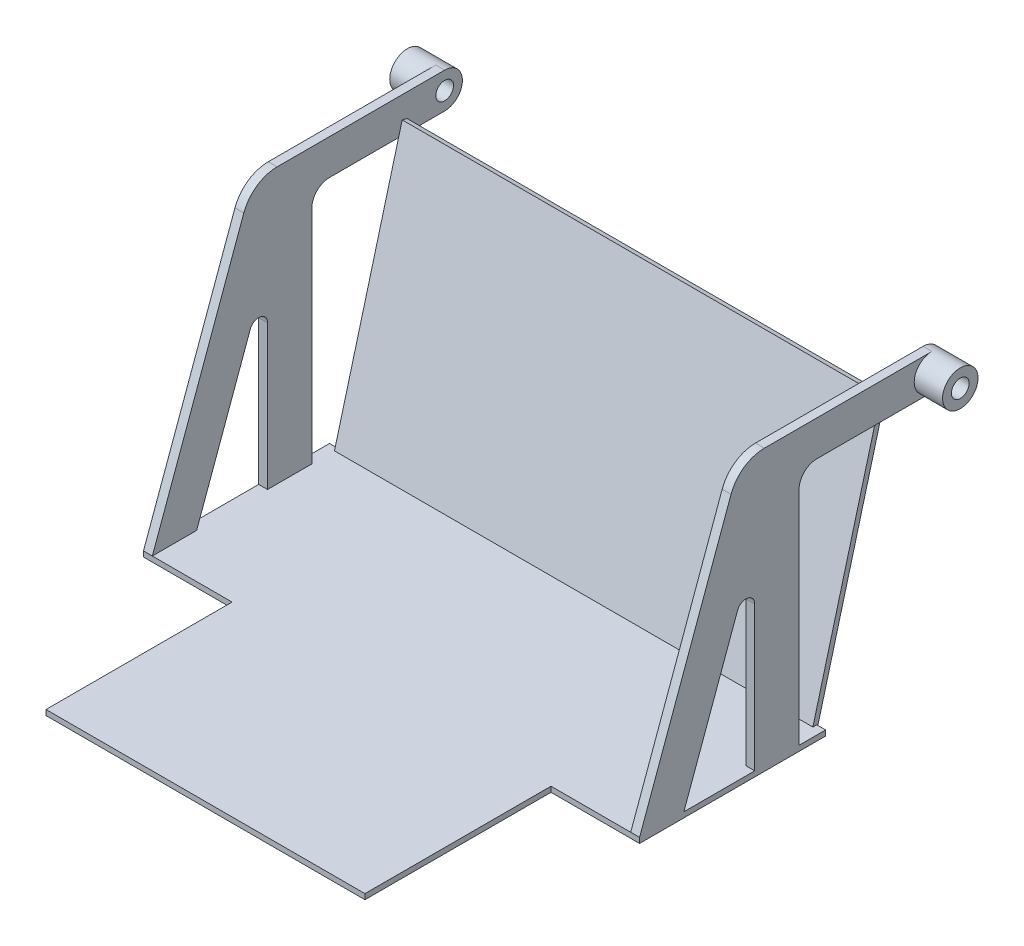
SolidWorks part; units mm, degrees
ref_plane "前视基准面" through (0, 0, 0) normal (0, 0, 1) x (1, 0, 0)
ref_plane "上视基准面" through (0, 0, 0) normal (0, 1, 0) x (1, 0, 0)
ref_plane "右视基准面" through (0, 0, 0) normal (1, 0, 0) x (0, 0, -1)
sketch "Sketch1" plane through (0, 0, 0) normal (0, 1, 0) x (1, 0, 0)
  line L0 (0, 0) -> (280, 0)
  line L1 (280, 0) -> (280, -100)
  line L2 (280, -100) -> (230, -100)
  line L3 (230, -100) -> (230, -210)
  line L4 (230, -210) -> (50, -210)
  line L5 (50, -210) -> (50, -100)
  line L6 (50, -100) -> (0, -100)
  line L7 (0, -100) -> (0, 0)
  dimension "D1" = 280
  dimension "D2" = 100
  dimension "D3" = 110
  dimension "D4" = 50
  dimension "D5" = 50
  dimension "D6" = 110
extrude "Boss-Extrude1" add sketch "Sketch1" along normal blind 3
sketch "Sketch2" plane through (0, 0, 0) normal (-1, 0, 0) x (0, 0, 1)
  line L0 (15, 0) -> (15, 3)
  line L1 (0, 0) -> (100, 0) construction
  line L2 (0, 3) -> (100, 3) construction
  line L6 (40, 3) -> (40, 0)
  line L7 (40, 0) -> (15, 0)
  line L8 (0, 3) -> (0, 0) construction
  line L10 (80, 3) -> (80, 0)
  line L11 (80, 0) -> (105, 0)
  line L12 (105, 0) -> (105, 3)
  line L15 (-60, 138) -> (5, 138)
  line L16 (15, 128) -> (15, 3)
  line L17 (40, 3) -> (40, 84.5427)
  line L18 (34.5805, 158) -> (-60, 158)
  line L19 (80, 3) -> (49.6985, 86.2528)
  line L20 (105, 3) -> (53.3743, 144.8404)
  arc A2 (-60, 158) -> (-60, 138) centre (-60, 148) ccw
  arc A3 (5, 138) -> (15, 128) centre (5, 128) cw
  arc A4 (53.3743, 144.8404) -> (34.5805, 158) centre (34.5805, 138) ccw
  arc A5 (40, 84.5427) -> (49.6985, 86.2528) centre (45, 84.5427) cw
  dimension "D5" = 20
  dimension "D8" = 70
  dimension "D9" = 10
  dimension "D10" = 20
  dimension "D11" = 5
  dimension "D1" = 15
  dimension "D2" = 25
  dimension "D3" = 60
  dimension "D4" = 145
  dimension "D6" = 40
  dimension "D7" = 25
extrude "Boss-Extrude2" add sketch "Sketch2" against normal through all
sketch "Sketch3" plane through (0, 0, 0) normal (0, 0, -1) x (-1, 0, 0)
  line L0 (-275, 3) -> (-275, 203)
  line L2 (-275, 203) -> (-5, 203)
  line L3 (-5, 203) -> (-5, 3)
  line L5 (-280, 128) -> (-280, 3) construction
  line L6 (0, 128) -> (0, 3) construction
  line L7 (-275, 3) -> (-5, 3)
  line L8 (0, 3) -> (-280, 3) construction
  dimension "D1" = 5
  dimension "D2" = 5
  dimension "D3" = 200
extrude "Cut-Extrude2" cut sketch "Sketch3" against normal through all both and the other way through all
sketch "Sketch4" plane through (0, 0, 0) normal (-1, 0, 0) x (0, 0, 1)
  circle A0 centre (-60, 148) radius 5
  dimension "D1" = 10
extrude "Cut-Extrude3" cut sketch "Sketch4" against normal through all both and the other way through all
sketch "Sketch5" plane through (0, 0, 0) normal (-1, 0, 0) x (0, 0, 1)
  circle A0 centre (-60, 148) radius 5
  circle A1 centre (-60, 148) radius 10
  dimension "D1" = 10
  dimension "D2" = 20
extrude "Boss-Extrude3" add sketch "Sketch5" along normal blind 16
sketch "Sketch6" plane through (280, 0, 0) normal (1, 0, 0) x (0, 0, -1)
  circle A0 centre (60, 148) radius 5
  circle A1 centre (60, 148) radius 10
  dimension "D1" = 10
  dimension "D2" = 20
extrude "Boss-Extrude4" add sketch "Sketch6" along normal blind 16
sketch "Sketch7" plane through (5, 0, 0) normal (1, 0, 0) x (0, 0, -1)
  line L0 (0, 0) -> (-3, 0)
  line L1 (-105, 0) -> (0, 0) construction
  line L2 (-3, 0) -> (36.0238, 145.6389)
  line L3 (36.0238, 145.6389) -> (38.8229, 144.8889)
  line L4 (38.8229, 144.8889) -> (0, 0)
  line L5 (-15, 3) -> (0, 3) construction
  dimension "D1" = 3
  dimension "D2" = 150
  dimension "D3" = 105
extrude "Boss-Extrude5" add sketch "Sketch7" along normal blind 270
